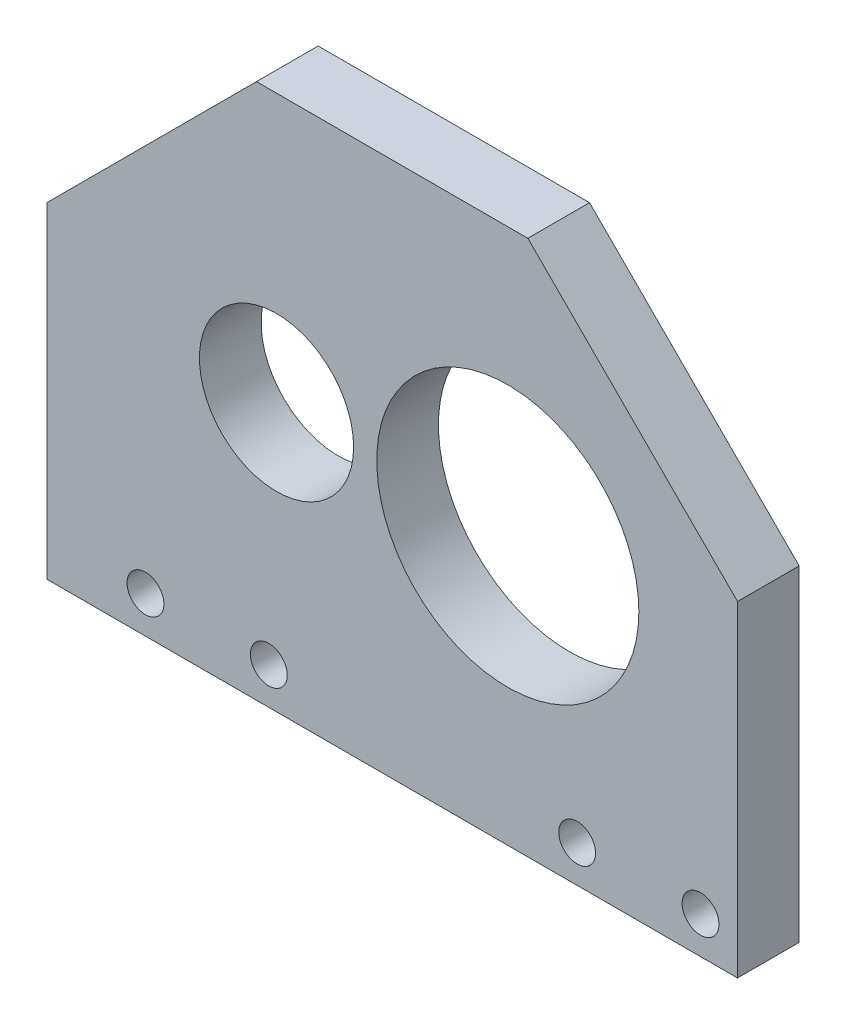
SolidWorks part; units mm, degrees
ref_plane "Front Plane" through (0, 0, 0) normal (0, 0, 1) x (1, 0, 0)
ref_plane "Top Plane" through (0, 0, 0) normal (0, 1, 0) x (1, 0, 0)
ref_plane "Right Plane" through (0, 0, 0) normal (1, 0, 0) x (0, 0, -1)
sketch "Sketch1" plane through (0, 0, 0) normal (0, 0, 1) x (1, 0, 0)
  line L1 (35.56, -27.5819) -> (-35.56, -27.5819)
  line L2 (35.56, -27.5819) -> (35.56, 27.5819)
  line L3 (35.56, 27.5819) -> (-35.56, 27.5819)
  line L4 (-35.56, -27.5819) -> (-35.56, 27.5819)
  line L5 (35.56, -27.5819) -> (-35.56, 27.5819) construction
  line L6 (35.56, 27.5819) -> (-35.56, -27.5819) construction
  circle A0 centre (11.9062, 0) radius 13.4937
  circle A1 centre (-11.9062, 0) radius 7.9375
  point P0 (0, 0)
  dimension "D3" = 26.9875
  dimension "D6" = 15.875
  dimension "D1" = 71.12
  dimension "D2" = 55.1637
  dimension "D4" = 0
  dimension "D5" = 0
  dimension "D7" = 11.9062
  dimension "D8" = 11.9062
extrude "Boss-Extrude1" add sketch "Sketch1" along normal blind 6.35
hole_wizard "#6 Clearance Hole1" positions "Sketch2" profile "Sketch3" hole size "#6" standard "ANSI Inch" end condition through all
sketch "Sketch2" plane through (0, 0, 6.35) normal (0, 0, 1) x (1, 0, 0)
  line L1 (-25.4, -23.7719) -> (-12.7, -23.7719)
  line L3 (19.05, -23.7719) -> (31.75, -23.7719)
  line L5 (-35.56, -27.5819) -> (35.56, -27.5819) construction
  line L6 (-35.56, 27.5819) -> (-35.56, -27.5819) construction
  line L7 (35.56, -27.5819) -> (35.56, 27.5819) construction
  point P0 (-25.4, -23.7719)
  point P2 (-12.7, -23.7719)
  point P4 (19.05, -23.7719)
  point P6 (31.75, -23.7719)
  dimension "D1" = 12.7
  dimension "D2" = 12.7
  dimension "D3" = 3.81
  dimension "D4" = 3.81
  dimension "D5" = 10.16
  dimension "D6" = 3.81
sketch "Sketch3" plane through (-25.4, -23.7719, 6.35) normal (1, 0, 0) x (0, -1, 0)
  line L0 (0, 0) -> (0, 6.35)
  line L1 (0, 6.35) -> (1.8986, 6.35)
  line L2 (1.8986, 6.35) -> (1.8986, 0)
  line L5 (1.8986, 0) -> (0, 0)
  line L11 (0, -6.35) -> (0, 107.95) construction
  dimension "Thru Hole Dia." = 3.7973
  dimension "Thru Hole Depth" = 6.35
sketch "Sketch4" plane through (0, 0, 6.35) normal (0, 0, 1) x (1, 0, 0)
  line L0 (-35.56, 5.9919) -> (-13.97, 27.5819)
  line L1 (-35.56, 27.5819) -> (-35.56, -27.5819) construction
  line L2 (35.56, 27.5819) -> (-35.56, 27.5819) construction
  line L3 (35.56, 5.9919) -> (13.97, 27.5819)
  line L4 (35.56, -27.5819) -> (35.56, 27.5819) construction
  line L5 (-35.56, 27.5819) -> (-35.56, 5.9919)
  line L6 (-13.97, 27.5819) -> (-35.56, 27.5819)
  line L7 (13.97, 27.5819) -> (35.56, 27.5819)
  line L8 (35.56, 27.5819) -> (35.56, 5.9919)
  dimension "D1" = 21.59
  dimension "D2" = 21.59
  dimension "D3" = 21.59
  dimension "D4" = 21.59
extrude "Cut-Extrude1" cut sketch "Sketch4" against normal through all
